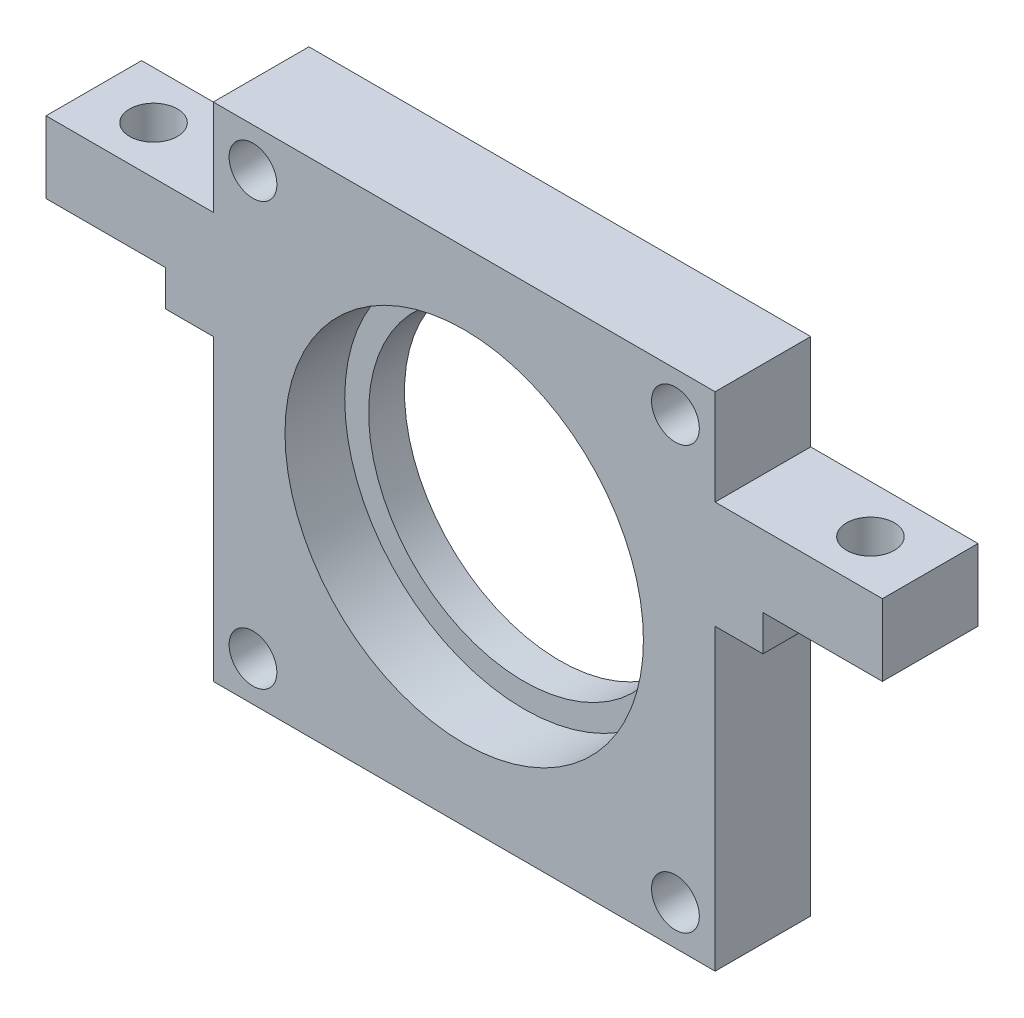
SolidWorks part; units mm, degrees
ref_plane "前视基准面" through (0, 0, 0) normal (0, 0, 1) x (1, 0, 0)
ref_plane "上视基准面" through (0, 0, 0) normal (0, 1, 0) x (1, 0, 0)
ref_plane "右视基准面" through (0, 0, 0) normal (1, 0, 0) x (0, 0, -1)
sketch "草图2" plane through (0, 0, 0) normal (0, 0, 1) x (1, 0, 0)
  line L0 (0, 31.8729) -> (0, -31.2987) construction
  line L1 (-25, 7) -> (-35, 7)
  line L2 (-21, 21) -> (21, 21)
  line L3 (-21, 21) -> (-21, 13)
  line L4 (-21, -21) -> (21, -21)
  line L5 (21, 21) -> (21, 13)
  line L6 (-35, 7) -> (-35, 13)
  line L7 (-35, 13) -> (-21, 13)
  line L8 (-21, 4) -> (-21, -21)
  line L9 (35, 13) -> (21, 13)
  line L10 (35, 7) -> (35, 13)
  line L11 (25, 7) -> (35, 7)
  line L12 (21, 4) -> (21, -21)
  line L13 (25, 4) -> (21, 4)
  line L15 (-25, 7) -> (-25, 4)
  line L16 (-25, 4) -> (-21, 4)
  line L18 (25, 7) -> (25, 4)
  dimension "D1" = 42
  dimension "D2" = 42
  dimension "D3" = 21
  dimension "D4" = 14
  dimension "D5" = 8
  dimension "D6" = 6
  dimension "D7" = 3
  dimension "D8" = 4
extrude "凸台-拉伸1" add sketch "草图2" along normal mid plane 8
sketch "草图3" plane through (0, 0, 4) normal (0, 0, 1) x (1, 0, 0)
  circle A0 centre (0, 0) radius 15
  dimension "D1" = 30
extrude "切除-拉伸1" cut sketch "草图3" against normal blind 5
sketch "草图4" plane through (0, 0, 4) normal (0, 0, 1) x (1, 0, 0)
  line L0 (0, 0) -> (-21, 21) construction
  circle A0 centre (0, 0) radius 25 construction
  circle A1 centre (-17.6777, 17.6777) radius 2
  circle A2 centre (17.6777, 17.6777) radius 2
  circle A3 centre (17.6777, -17.6777) radius 2
  circle A4 centre (-17.6777, -17.6777) radius 2
  dimension "D1" = 50
  dimension "D2" = 4
  dimension "D3" = 4
extrude "切除-拉伸2" cut sketch "草图4" against normal through all
sketch "草图5" plane through (0, 13, 0) normal (0, 1, 0) x (1, 0, 0)
  line L0 (0, 4) -> (0, -4) construction
  line L1 (21, 4) -> (-21, 4) construction
  line L2 (21, -4) -> (-21, -4) construction
  line L3 (-35, -4) -> (-35, 4) construction
  circle A0 centre (-30, 0) radius 2
  circle A1 centre (30, 0) radius 2
  dimension "D1" = 4
  dimension "D2" = 5
extrude "切除-拉伸3" cut sketch "草图5" against normal through all
sketch "草图6" plane through (0, 0, -1) normal (0, 0, 1) x (1, 0, 0)
  circle A0 centre (0, 0) radius 13
  dimension "D1" = 26
extrude "切除-拉伸4" cut sketch "草图6" against normal through all
